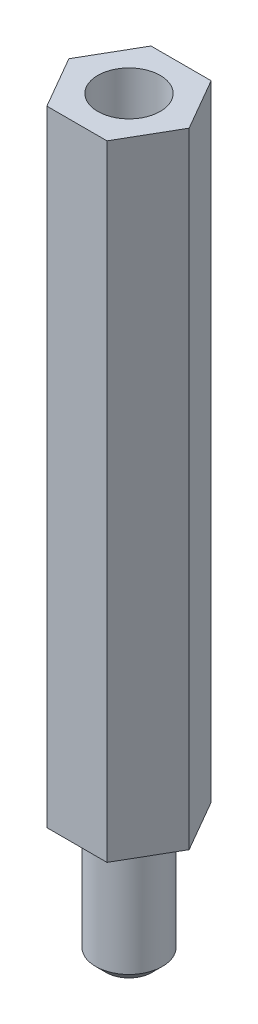
SolidWorks part; units mm, degrees
material "Alloy Steel"
ref_plane "Front Plane" through (0, 0, 0) normal (0, 0, 1) x (1, 0, 0)
ref_plane "Top Plane" through (0, 0, 0) normal (0, 1, 0) x (1, 0, 0)
ref_plane "Right Plane" through (0, 0, 0) normal (1, 0, 0) x (0, 0, -1)
sketch "Sketch1" plane through (0, 0, 0) normal (0, 1, 0) x (1, 0, 0)
  line L0 (0, 0) -> (0, 2.5) construction
  line L1 (-1.4434, 2.5) -> (1.4434, 2.5)
  line L2 (1.4434, 2.5) -> (2.8868, 0)
  line L3 (2.8868, 0) -> (1.4434, -2.5)
  line L4 (1.4434, -2.5) -> (-1.4434, -2.5)
  line L5 (-1.4434, -2.5) -> (-2.8868, 0)
  line L6 (-2.8868, 0) -> (-1.4434, 2.5)
  circle A0 centre (0, 0) radius 1.5
  dimension "D2" = 3
  dimension "D1" = 5
  dimension "D3" = 2.5
extrude "Extrude1" add sketch "Sketch1" along normal blind 30
sketch "Sketch2" plane through (0, 0, 0) normal (0, -1, 0) x (1, 0, 0)
  circle A0 centre (0, 0) radius 1.6
  dimension "D1" = 3.2
extrude "Extrude2" add sketch "Sketch2" along normal blind 6 and the other way blind 22
chamfer "Chamfer1" distance 0.5 angle 45 1 edges at (0, -6, -1.6)
fillet "Fillet1" radius 0.5 1 edges at (0, 0, 1.6)
fillet "Fillet2" radius 1 1 edges at (0, 22, -1.5)
